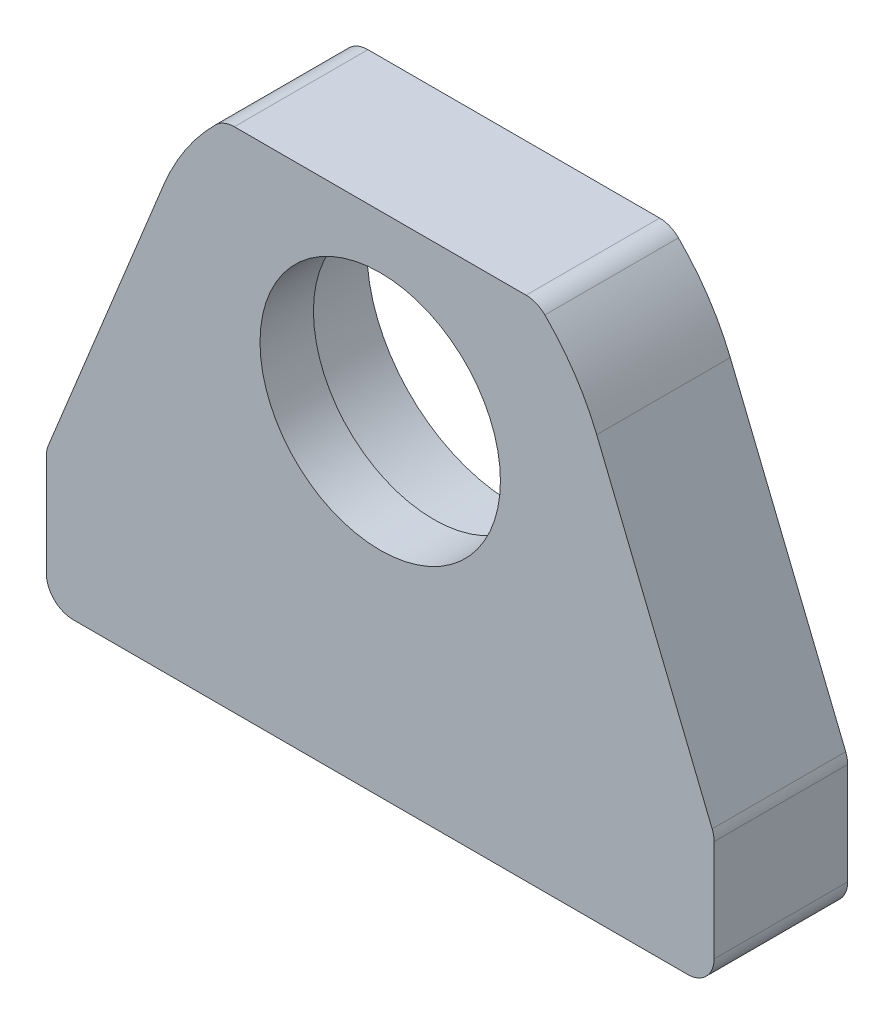
SolidWorks part; units mm, degrees
material "5052-H34"
ref_plane "正面" through (0, 0, 0) normal (0, 0, 1) x (1, 0, 0)
ref_plane "平面" through (0, 0, 0) normal (0, 1, 0) x (1, 0, 0)
ref_plane "右側面" through (0, 0, 0) normal (1, 0, 0) x (0, 0, -1)
sketch "ｽｹｯﾁ1" plane through (0, 0, 0) normal (0, 0, 1) x (1, 0, 0)
  line L0 (0, 0) -> (0, -20) construction
  line L1 (-25, -15) -> (-16.2086, 6.5977)
  line L3 (-25, -15) -> (-25, -25)
  line L4 (-25, -25) -> (25, -25)
  line L5 (25, -15) -> (25, -25)
  line L6 (-25, -15) -> (25, -25) construction
  line L7 (-25, -25) -> (25, -15) construction
  line L8 (25, -15) -> (16.2086, 6.5977)
  line L9 (0, 0) -> (0, 13) construction
  line L10 (-11.7154, 13) -> (11.7154, 13)
  arc A0 (16.2086, 6.5977) -> (11.7154, 13) centre (0, 0) ccw
  arc A1 (-11.7154, 13) -> (-16.2086, 6.5977) centre (0, 0) ccw
  dimension "D1" = 35
  dimension "D2" = 10
  dimension "D3" = 50
  dimension "D4" = 20
  dimension "D5" = 13
extrude "ﾎﾞｽ - 押し出し1" add sketch "ｽｹｯﾁ1" along normal blind 10
sketch "ｽｹｯﾁ2" plane through (0, 0, 0) normal (0, 0, -1) x (-1, 0, 0)
  circle A0 centre (0, 0) radius 11
  dimension "D1" = 22
extrude "ｶｯﾄ - 押し出し1" cut sketch "ｽｹｯﾁ2" against normal blind 6
sketch "ｽｹｯﾁ3" plane through (0, -25, 0) normal (0, -1, 0) x (1, 0, 0)
  line L0 (0, 0) -> (0, 10) construction
  line L1 (-25, 0) -> (25, 0) construction
  line L2 (-25, 10) -> (25, 10) construction
  line L3 (0, 5) -> (-20, 5) construction
  circle A0 centre (-20, 5) radius 1.65
  circle A1 centre (20, 5) radius 1.65
  dimension "D1" = 3.3
  dimension "D2" = 40
extrude "ｶｯﾄ - 押し出し2" cut sketch "ｽｹｯﾁ3" against normal blind 10
sketch "ｽｹｯﾁ4" plane through (0, 0, 6) normal (0, 0, -1) x (-1, 0, 0)
  circle A0 centre (0, 0) radius 9
  dimension "D1" = 18
extrude "ｶｯﾄ - 押し出し3" cut sketch "ｽｹｯﾁ4" against normal through all
fillet "ﾌｨﾚｯﾄ1" radius 2 6 edges at (25, -25, 5) (-25, -25, 5) (-25, -15, 5) (25, -15, 5) (11.7154, 13, 5) (-11.7154, 13, 5)
